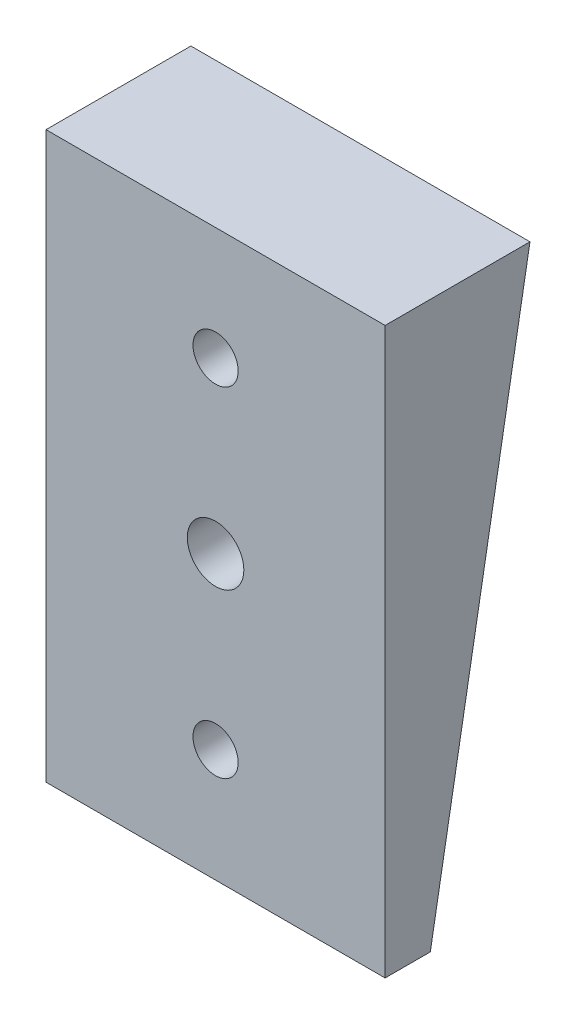
SolidWorks part; units mm, degrees
ref_plane "Front Plane" through (0, 0, 0) normal (0, 0, 1) x (1, 0, 0)
ref_plane "Top Plane" through (0, 0, 0) normal (0, 1, 0) x (1, 0, 0)
ref_plane "Right Plane" through (0, 0, 0) normal (1, 0, 0) x (0, 0, -1)
sketch "Sketch2" plane through (0, 0, 0) normal (1, 0, 0) x (0, 0, -1)
  line L0 (4, 50) -> (21.6327, 50)
  line L1 (-4, 50) -> (4, 50)
  line L2 (-4, 50) -> (-4, -50)
  line L3 (-4, -50) -> (4, -50)
  line L4 (4, 50) -> (4, -50) construction
  line L5 (-4, 50) -> (4, -50) construction
  line L6 (-4, -50) -> (4, 50) construction
  line L7 (21.6327, 50) -> (4, -50)
  point P0 (0, 0)
  dimension "D1" = 8
  dimension "D2" = 100
  dimension "D3" = 10
extrude "Boss-Extrude1" add sketch "Sketch2" along normal mid plane 60
sketch "Sketch3" plane through (0, 0, 4) normal (0, 0, 1) x (1, 0, 0)
  line L0 (0, 30) -> (0, -30) construction
  circle A0 centre (0, -30) radius 4
  circle A1 centre (0, 30) radius 4
  circle A2 centre (0, 0) radius 5
  point P4 (0, 0)
  dimension "D2" = 10
  dimension "D3" = 8
  dimension "D1" = 60
extrude "Cut-Extrude1" cut sketch "Sketch3" against normal blind 60
